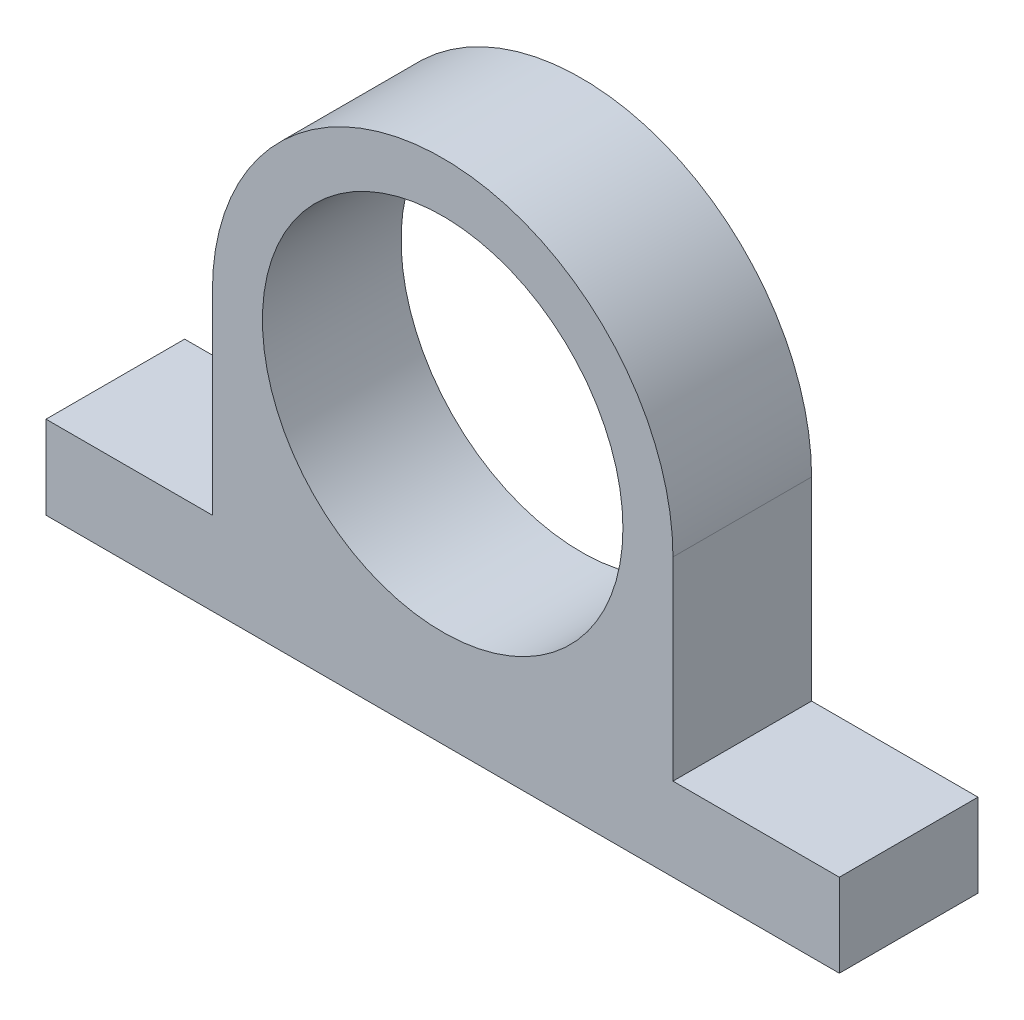
SolidWorks part; units mm, degrees
ref_plane "Front Plane" through (0, 0, 0) normal (0, 0, 1) x (1, 0, 0)
ref_plane "Top Plane" through (0, 0, 0) normal (0, 1, 0) x (1, 0, 0)
ref_plane "Right Plane" through (0, 0, 0) normal (1, 0, 0) x (0, 0, -1)
sketch "Sketch1" plane through (0, 0, 0) normal (0, 0, 1) x (1, 0, 0)
  line L18 (-119.3888, -28.0485) -> (-119.3888, -98.0485)
  line L19 (-119.3888, -98.0485) -> (-179.3888, -98.0485)
  line L20 (-179.3888, -98.0485) -> (-179.3888, -128.0485)
  line L21 (46.6902, -28.0485) -> (46.6902, -98.0485)
  line L23 (46.6902, -98.0485) -> (106.6902, -98.0485)
  line L24 (106.6902, -98.0485) -> (106.6902, -128.0485)
  line L25 (-179.3888, -128.0485) -> (106.6902, -128.0485)
  circle A1 centre (-36.3493, -28.0485) radius 65
  arc A3 (46.6902, -28.0485) -> (-119.3888, -28.0485) centre (-36.3493, -28.0485) ccw
  point P11 (-36.3493, -28.0485)
  point P15 (-36.3493, -28.0485)
  dimension "D3" = 70
  dimension "D1" = 130
  dimension "D2" = 70
  dimension "D4" = 60
  dimension "D5" = 30
  dimension "D6" = 60
  dimension "D7" = 30
extrude "Boss-Extrude3" add sketch "Sketch1" along normal blind 50
